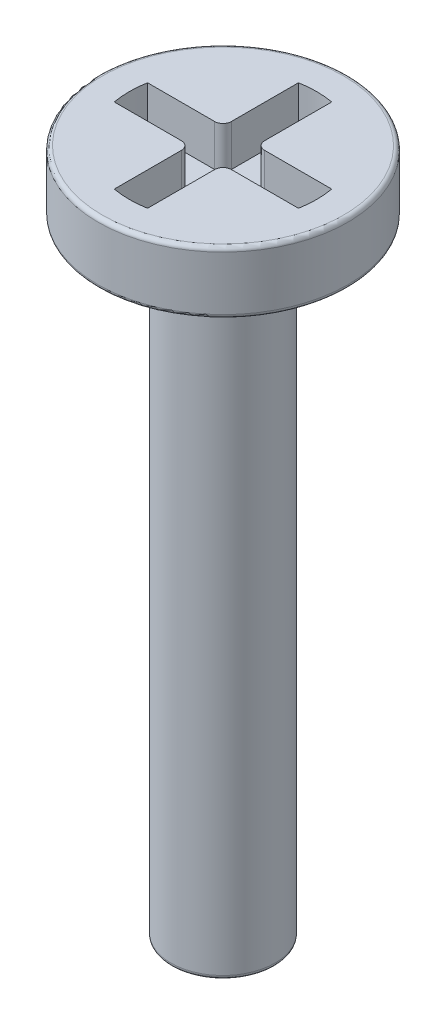
SolidWorks part; units mm, degrees
ref_plane "Front Plane" through (0, 0, 0) normal (0, 0, 1) x (1, 0, 0)
ref_plane "Top Plane" through (0, 0, 0) normal (0, 1, 0) x (1, 0, 0)
ref_plane "Right Plane" through (0, 0, 0) normal (1, 0, 0) x (0, 0, -1)
sketch "Sketch1" plane through (0, 0, 0) normal (0, 0, 1) x (1, 0, 0)
  line L0 (0, 0) -> (-3, 0)
  line L1 (-3, 0) -> (-3, -1.5)
  line L2 (-3, -1.5) -> (-1.25, -1.5)
  line L3 (-1.25, -1.5) -> (-1.25, -16.5)
  line L4 (-1.25, -16.5) -> (0, -16.5)
  line L5 (0, -16.5) -> (0, 0)
  line L6 (0, 14.9129) -> (0, 0) construction
  dimension "D1" = 2.5
  dimension "D2" = 3
  dimension "D3" = 3
  dimension "D4" = 1.5
  dimension "D5" = 15
revolve "Revolve1" add sketch "Sketch1" angle 360 about L6
fillet "Fillet1" radius 0.1 3 edges at (0, -16.5, 1.25) (0, 0, 3) (0, -1.5, 3)
sketch "Sketch2" plane through (0, 0, 0) normal (0, 1, 0) x (1, 0, 0)
  line L0 (0, 2.25) -> (0, -2.25) construction
  line L1 (-2.25, 0) -> (2.25, 0) construction
  line L2 (-2.2142, -0.4) -> (-0.6, -0.4)
  line L3 (-2.2142, 0.4) -> (-0.6, 0.4)
  line L4 (-0.4, 2.2142) -> (-0.4, 0.6)
  line L5 (0.4, 2.2142) -> (0.4, 0.6)
  line L6 (-0.4, 2.25) -> (-0.4, -2.25) construction
  line L7 (0.4, 2.25) -> (0.4, -2.25) construction
  line L8 (-2.25, -0.4) -> (2.25, -0.4) construction
  line L9 (-2.25, 0.4) -> (2.25, 0.4) construction
  line L10 (0.6, 0.4) -> (2.2142, 0.4)
  line L11 (0.4, -0.6) -> (0.4, -2.2142)
  line L12 (-0.4, -0.6) -> (-0.4, -2.2142)
  line L13 (0.6, -0.4) -> (2.2142, -0.4)
  arc A0 (-2.2142, 0.4) -> (-2.2142, -0.4) centre (0, 0) ccw
  arc A1 (0.4, 2.2142) -> (-0.4, 2.2142) centre (0, 0) ccw
  arc A2 (-0.4, -2.2142) -> (0.4, -2.2142) centre (0, 0) ccw
  arc A3 (2.2142, -0.4) -> (2.2142, 0.4) centre (0, 0) ccw
  arc A4 (-0.6, -0.4) -> (-0.4, -0.6) centre (-0.6, -0.6) cw
  arc A5 (0.4, -0.6) -> (0.6, -0.4) centre (0.6, -0.6) cw
  arc A6 (0.6, 0.4) -> (0.4, 0.6) centre (0.6, 0.6) cw
  arc A7 (-0.4, 0.6) -> (-0.6, 0.4) centre (-0.6, 0.6) cw
  dimension "D1" = 4.5
  dimension "D6" = 0.2
  dimension "D2" = 0.4
  dimension "D3" = 0.4
  dimension "D4" = 0.4
  dimension "D5" = 0.4
extrude "Cut-Extrude1" cut sketch "Sketch2" against normal blind 1
